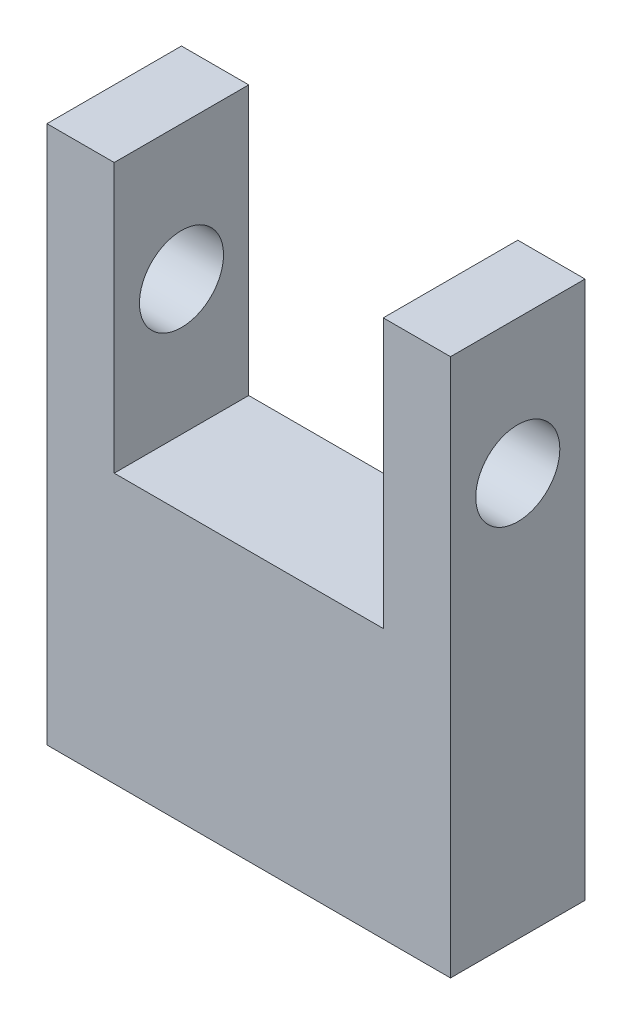
SolidWorks part; units mm, degrees
ref_plane "Front Plane" through (0, 0, 0) normal (0, 0, 1) x (1, 0, 0)
ref_plane "Top Plane" through (0, 0, 0) normal (0, 1, 0) x (1, 0, 0)
ref_plane "Right Plane" through (0, 0, 0) normal (1, 0, 0) x (0, 0, -1)
sketch "Sketch1" plane through (0, 0, 0) normal (0, 0, 1) x (1, 0, 0)
  line L0 (-38.1, 0) -> (38.1, 0)
  line L1 (38.1, 0) -> (38.1, 101.6)
  line L2 (38.1, 101.6) -> (25.4, 101.6)
  line L3 (25.4, 101.6) -> (25.4, 50.8)
  line L4 (25.4, 50.8) -> (-25.4, 50.8)
  line L5 (0, 50.8) -> (0, 0) construction
  line L6 (-25.4, 101.6) -> (-25.4, 50.8)
  line L7 (-38.1, 101.6) -> (-25.4, 101.6)
  line L8 (-38.1, 0) -> (-38.1, 101.6)
  dimension "D1" = 50.8
  dimension "D2" = 50.8
  dimension "D3" = 12.7
  dimension "D4" = 50.8
extrude "Boss-Extrude1" add sketch "Sketch1" along normal mid plane 25.4
sketch "Sketch2" plane through (0, 0, 0) normal (1, 0, 0) x (0, 0, -1)
  line L0 (-12.7, 101.6) -> (12.7, 101.6) construction
  circle A0 centre (0, 76.2) radius 7.9375
  dimension "D1" = 15.875
  dimension "D2" = 25.4
extrude "Cut-Extrude1" cut sketch "Sketch2" against normal through all both and the other way through all
